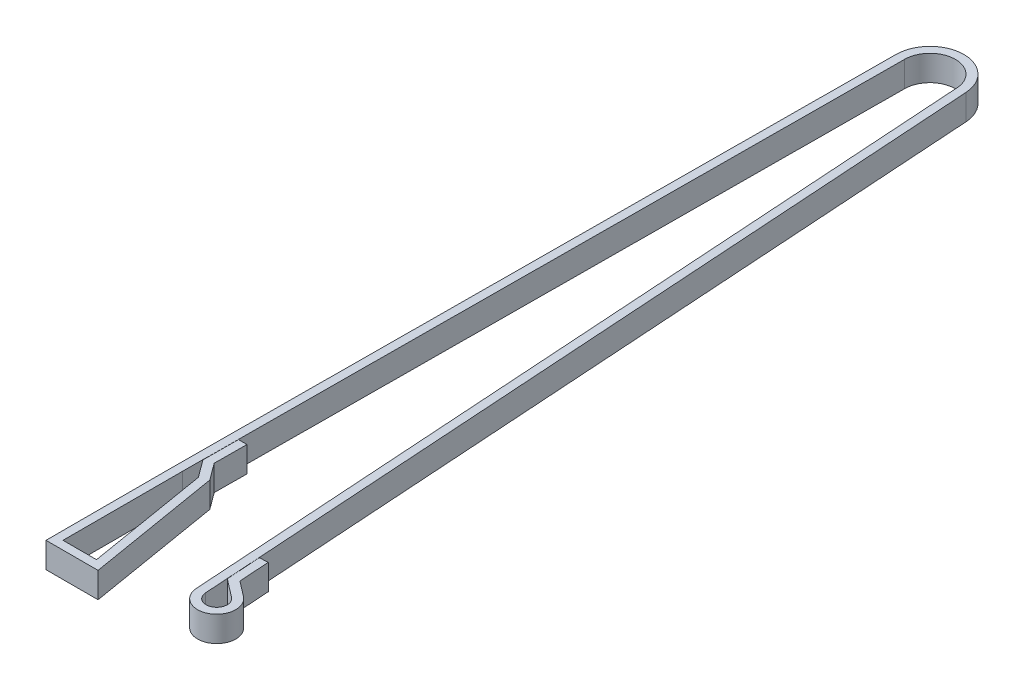
SolidWorks part; units mm, degrees
ref_plane "Front Plane" through (0, 0, 0) normal (0, 0, 1) x (1, 0, 0)
ref_plane "Top Plane" through (0, 0, 0) normal (0, 1, 0) x (1, 0, 0)
ref_plane "Right Plane" through (0, 0, 0) normal (1, 0, 0) x (0, 0, -1)
sketch "Sketch1" plane through (0, 0, 0) normal (0, 1, 0) x (1, 0, 0)
  line L0 (0, -29.2) -> (0, 0)
  line L1 (0, 0) -> (1.0001, 169.0414)
  line L2 (14.9851, 169.4563) -> (27.5074, -22.2282)
  line L3 (33.132, -19.2243) -> (29.1666, -16.1786)
  line L4 (29.1666, -16.1786) -> (28.6699, -8.5756)
  line L5 (0, -29.2) -> (10.078, -29.2)
  line L6 (10.078, -29.2) -> (5.0474, 0.9837)
  line L8 (2.0797, 5.0076) -> (2.127, 13.0076)
  line L11 (2.0797, 5.0076) -> (5.0474, 0.9837)
  arc A2 (1.0001, 169.0414) -> (14.9851, 169.4563) centre (8, 169) cw
  arc A3 (27.5074, -22.2282) -> (33.132, -19.2243) centre (31, -22) ccw
  dimension "D14" = 7
  dimension "D15" = 3.5
  dimension "D1" = 29.2
  dimension "D5" = 0
  dimension "D6" = 0
  dimension "D12" = 2.05
  dimension "D13" = 2.05
  dimension "D2" = 8
  dimension "D9" = 8
  dimension "D3" = 31
  dimension "D4" = 10.078
  dimension "D16" = 5
  dimension "D7" = 30.6
  dimension "D11" = 5
  dimension "D8" = 198.2
  dimension "D10" = 191
extrude "Extrude-Thin3" add sketch "Sketch1" along normal mid plane 6 thin thin type mid plane wall 2
equation "\"D10@Sketch1\"=389.2-\"D8@Sketch1\""
